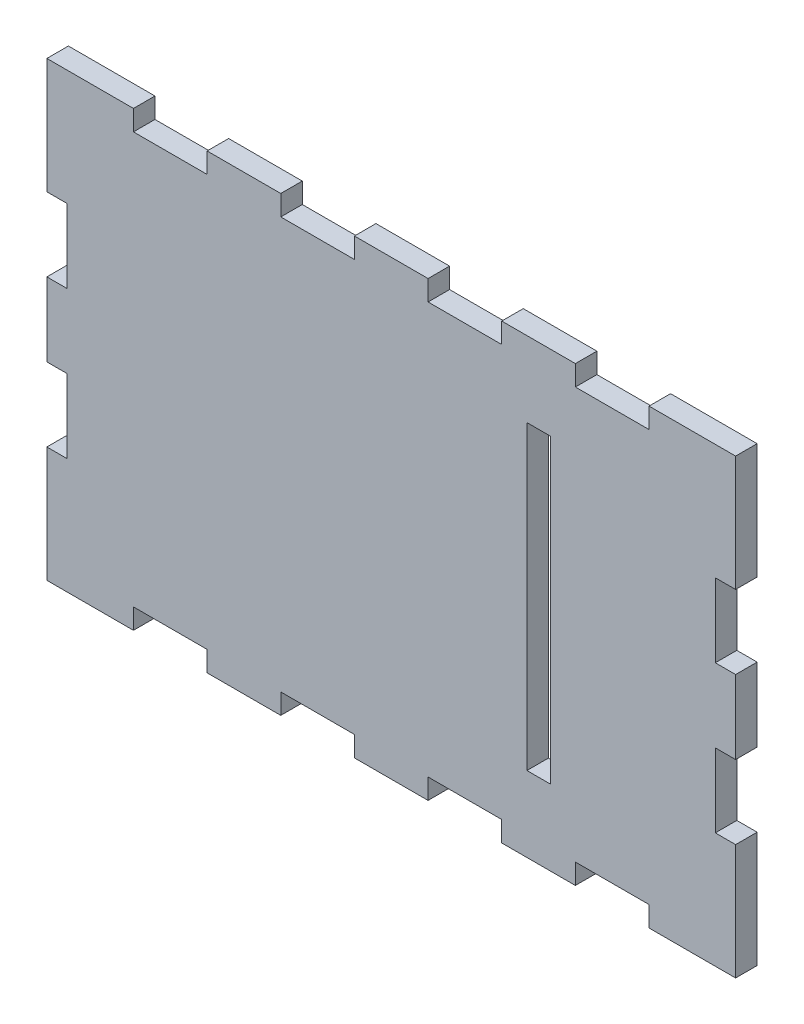
SolidWorks part; units mm, degrees
ref_plane "Front Plane" through (0, 0, 0) normal (0, 0, 1) x (1, 0, 0)
ref_plane "Top Plane" through (0, 0, 0) normal (0, 1, 0) x (1, 0, 0)
ref_plane "Right Plane" through (0, 0, 0) normal (1, 0, 0) x (0, 0, -1)
sketch "Sketch3" plane through (0, 0, 0) normal (0, 0, 1) x (1, 0, 0)
  line L162 (0, 77.5398) -> (0, 55.8102)
  line L163 (0, 55.8102) -> (5.9944, 55.8102)
  line L164 (5.9944, 55.8102) -> (5.9944, 34.0804)
  line L165 (5.9944, 34.0804) -> (0, 34.0804)
  line L166 (0, 34.0804) -> (0, 12.3508)
  line L167 (0, 12.3508) -> (0, 0)
  line L168 (0, 0) -> (25.5461, 0)
  line L169 (25.5461, 0) -> (25.5461, 5.9944)
  line L170 (25.5461, 5.9944) -> (47.2757, 5.9944)
  line L171 (47.2757, 5.9944) -> (47.2757, 0)
  line L172 (47.2757, 0) -> (69.0054, 0)
  line L173 (69.0054, 0) -> (69.0054, 5.9944)
  line L174 (69.0054, 5.9944) -> (90.7352, 5.9944)
  line L175 (90.7352, 5.9944) -> (90.7352, 0)
  line L176 (90.7352, 0) -> (112.4648, 0)
  line L177 (112.4648, 0) -> (112.4648, 5.9944)
  line L178 (112.4648, 5.9944) -> (134.1945, 5.9944)
  line L179 (134.1945, 5.9944) -> (134.1945, 0)
  line L180 (134.1945, 0) -> (155.9242, 0)
  line L181 (155.9242, 0) -> (155.9242, 5.9944)
  line L182 (155.9242, 5.9944) -> (177.6539, 5.9944)
  line L183 (177.6539, 5.9944) -> (177.6539, 0)
  line L184 (177.6539, 0) -> (203.2, 0)
  line L185 (203.2, 0) -> (203.2, 34.0804)
  line L186 (203.2, 34.0804) -> (197.2056, 34.0804)
  line L187 (197.2056, 34.0804) -> (197.2056, 55.8102)
  line L188 (197.2056, 55.8102) -> (203.2, 55.8102)
  line L189 (203.2, 55.8102) -> (203.2, 77.5398)
  line L190 (203.2, 77.5398) -> (197.2056, 77.5398)
  line L191 (197.2056, 77.5398) -> (197.2056, 99.2695)
  line L192 (197.2056, 99.2695) -> (203.2, 99.2695)
  line L193 (203.2, 99.2695) -> (203.2, 120.9993)
  line L194 (203.2, 120.9993) -> (203.2, 133.35)
  line L195 (203.2, 133.35) -> (177.6539, 133.35)
  line L196 (177.6539, 133.35) -> (177.6539, 127.3556)
  line L197 (177.6539, 127.3556) -> (155.9242, 127.3556)
  line L198 (155.9242, 127.3556) -> (155.9242, 133.35)
  line L199 (155.9242, 133.35) -> (134.1945, 133.35)
  line L200 (134.1945, 133.35) -> (134.1945, 127.3556)
  line L201 (134.1945, 127.3556) -> (112.4648, 127.3556)
  line L202 (112.4648, 127.3556) -> (112.4648, 133.35)
  line L203 (112.4648, 133.35) -> (90.7352, 133.35)
  line L204 (90.7352, 133.35) -> (90.7352, 127.3556)
  line L205 (90.7352, 127.3556) -> (69.0054, 127.3556)
  line L206 (69.0054, 127.3556) -> (69.0054, 133.35)
  line L207 (69.0054, 133.35) -> (47.2757, 133.35)
  line L208 (47.2757, 133.35) -> (47.2757, 127.3556)
  line L209 (47.2757, 127.3556) -> (25.5461, 127.3556)
  line L210 (25.5461, 127.3556) -> (25.5461, 133.35)
  line L211 (25.5461, 133.35) -> (0, 133.35)
  line L212 (0, 133.35) -> (0, 99.2695)
  line L213 (0, 99.2695) -> (5.9944, 99.2695)
  line L214 (5.9944, 99.2695) -> (5.9944, 77.5398)
  line L215 (5.9944, 77.5398) -> (0, 77.5398)
extrude "Boss-Extrude1" add sketch "Sketch3" along normal blind 6.35
sketch "Sketch4" plane through (0, 0, 6.35) normal (0, 0, 1) x (1, 0, 0)
  line L0 (145.0594, 133.35) -> (145.0594, 0) construction
  line L1 (141.6294, 111.125) -> (148.5179, 111.125)
  line L2 (141.6294, 111.125) -> (141.6294, 22.225)
  line L3 (141.6294, 22.225) -> (148.5179, 22.225)
  line L4 (148.5179, 111.125) -> (148.5179, 22.225)
  line L7 (155.9242, 133.35) -> (134.1945, 133.35) construction
  line L8 (134.1945, 0) -> (155.9242, 0) construction
  line L9 (141.6294, 66.675) -> (148.5179, 66.675) construction
  dimension "D1" = 6.8885
  dimension "D2" = 88.9
  dimension "D3" = 3.43
  dimension "D4" = 66.675
extrude "Cut-Extrude1" cut sketch "Sketch4" against normal up to surface (6.35 mm away) up to face at (101.6, 66.675, 0)
